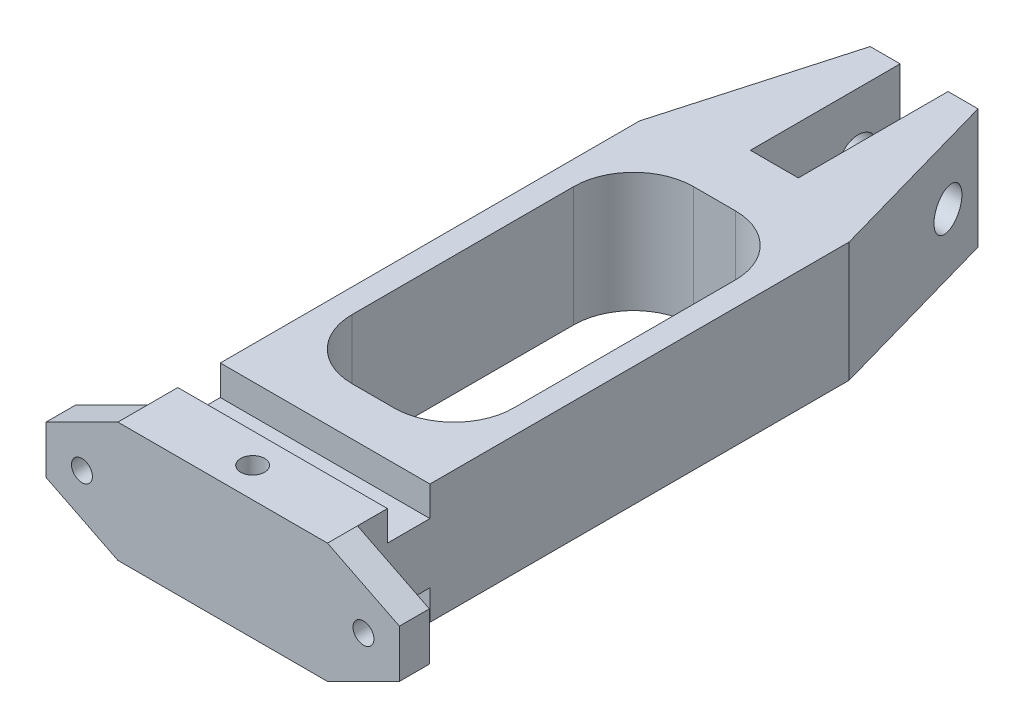
SolidWorks part; units mm, degrees
ref_plane "Alzado" through (0, 0, 0) normal (0, 0, 1) x (1, 0, 0)
ref_plane "Planta" through (0, 0, 0) normal (0, 1, 0) x (1, 0, 0)
ref_plane "Vista lateral" through (0, 0, 0) normal (1, 0, 0) x (0, 0, -1)
sketch "Croquis1" plane through (0, 0, 0) normal (1, 0, 0) x (0, 0, -1)
  line L8 (0, 10) -> (0, -10)
  line L9 (0, 0) -> (18.6556, 0) construction
  line L10 (10, -10) -> (10, -5)
  line L11 (0, 10) -> (10, 10)
  line L12 (10, 10) -> (10, 5)
  line L13 (10, 5) -> (17.1, 5)
  line L14 (17.1, 5) -> (17.1, 10)
  line L15 (17.1, 10) -> (117.1, 10)
  line L16 (117.1, 10) -> (117.1, -10)
  line L21 (10, -10) -> (0, -10)
  line L23 (17.1, -5) -> (17.1, -10)
  line L24 (17.1, -10) -> (117.1, -10)
  line L25 (10, -10) -> (17.1, -10) construction
  line L26 (117.1, 0) -> (110.1, 0) construction
  line L29 (17.1, -5) -> (10, -5)
  circle A1 centre (110.1, 0) radius 3.25
  point P11 (19.3317, -5)
  dimension "D6" = 6.5
  dimension "D1" = 20
  dimension "D2" = 10
  dimension "D3" = 5
  dimension "D4" = 7.1
  dimension "D5" = 100
  dimension "D7" = 7
extrude "Saliente-Extruir1" add sketch "Croquis1" along normal blind 35
sketch "Croquis2" plane through (0, 10, 0) normal (0, 1, 0) x (1, 0, 0)
  line L0 (21.5, 117.1) -> (21.5, 92.1)
  line L1 (35, 117.1) -> (0, 117.1) construction
  line L2 (21.5, 92.1) -> (13.5, 92.1)
  line L3 (13.5, 92.1) -> (13.5, 117.1)
  line L4 (13.5, 117.1) -> (21.5, 117.1)
  line L5 (17.5, 117.1) -> (17.5, 92.1) construction
  dimension "D1" = 8
  dimension "D2" = 25
extrude "Cortar-Extruir1" cut sketch "Croquis2" against normal up to next
sketch "Croquis4" plane through (0, 10, 0) normal (0, 1, 0) x (1, 0, 0)
  line L0 (13.5, 92.1) -> (0, 92.1) construction
  line L5 (0, 117.1) -> (0, 17.1) construction
  line L6 (35, 17.1) -> (0, 17.1) construction
  line L7 (35, 117.1) -> (35, 17.1) construction
  line L8 (4, 25.1) -> (31, 25.1)
  line L9 (4, 25.1) -> (4, 82.1)
  line L10 (4, 82.1) -> (31, 82.1)
  line L11 (31, 25.1) -> (31, 82.1)
  line L12 (4, 25.1) -> (31, 82.1) construction
  line L13 (4, 82.1) -> (31, 25.1) construction
  line L14 (17.5, 92.1) -> (17.5, 53.6) construction
  line L15 (13.5, 92.1) -> (21.5, 92.1) construction
  point P5 (17.5, 53.6)
  dimension "D1" = 4
  dimension "D2" = 10
  dimension "D3" = 8
extrude "Cortar-Extruir2" cut sketch "Croquis4" against normal through all
sketch "Croquis5" plane through (0, 10, 0) normal (0, 1, 0) x (1, 0, 0)
  line L0 (8.5, 117.1) -> (0, 87.1)
  line L1 (13.5, 117.1) -> (0, 117.1) construction
  line L2 (0, 117.1) -> (0, 17.1) construction
  line L3 (8.5, 117.1) -> (0, 117.1)
  line L4 (0, 117.1) -> (0, 87.1)
  line L5 (13.5, 117.1) -> (13.5, 92.1) construction
  line L6 (31, 82.1) -> (4, 82.1) construction
  dimension "D1" = 5
  dimension "D2" = 5
extrude "Cortar-Extruir3" cut sketch "Croquis5" against normal up to next
ref_plane "Plano1" through (17.5, 0, 0) normal (1, 0, 0) x (0, 0, -1)
mirror "Simetría1" about plane through (17.5, 0, 0) normal (1, 0, 0) of "Cortar-Extruir3"
sketch "Croquis9" plane through (0, 0, 0) normal (0, 0, 1) x (1, 0, 0)
  line L0 (0, 10) -> (-12, 4)
  line L1 (-12, 4) -> (-12, -4)
  line L2 (-12, -4) -> (0, -10)
  line L3 (0, 10) -> (0, -10) construction
  line L4 (-12, 4) -> (0, -4) construction
  line L5 (-12, 0) -> (-6, 0) construction
  line L6 (0, 10) -> (0, -10)
  circle A0 centre (-6, 0) radius 1.75
  point P10 (0, -4)
  dimension "D3" = 3.5
  dimension "D1" = 12
  dimension "D2" = 8
extrude "Saliente-Extruir3" add sketch "Croquis9" against normal blind 5
chamfer "Chaflán1" distance 1.5 angle 45 1 edges at (-4.25, 0, -5)
mirror "Simetría3" about plane through (17.5, 0, 0) normal (1, 0, 0) of "Chaflán1", "Saliente-Extruir3"
sketch "Croquis7" plane through (0, 10, 0) normal (0, 1, 0) x (1, 0, 0)
  line L0 (0, 0) -> (35, 10) construction
  circle A0 centre (17.5, 5) radius 2
  point P6 (17.5, 5)
  dimension "D1" = 4
extrude "Enganche" cut sketch "Croquis7" against normal up to next
fillet "Redondeo1" radius 10 4 edges at (31, 0, -25.1) (4, 0, -25.1) (31, 0, -82.1) (4, 0, -82.1)
